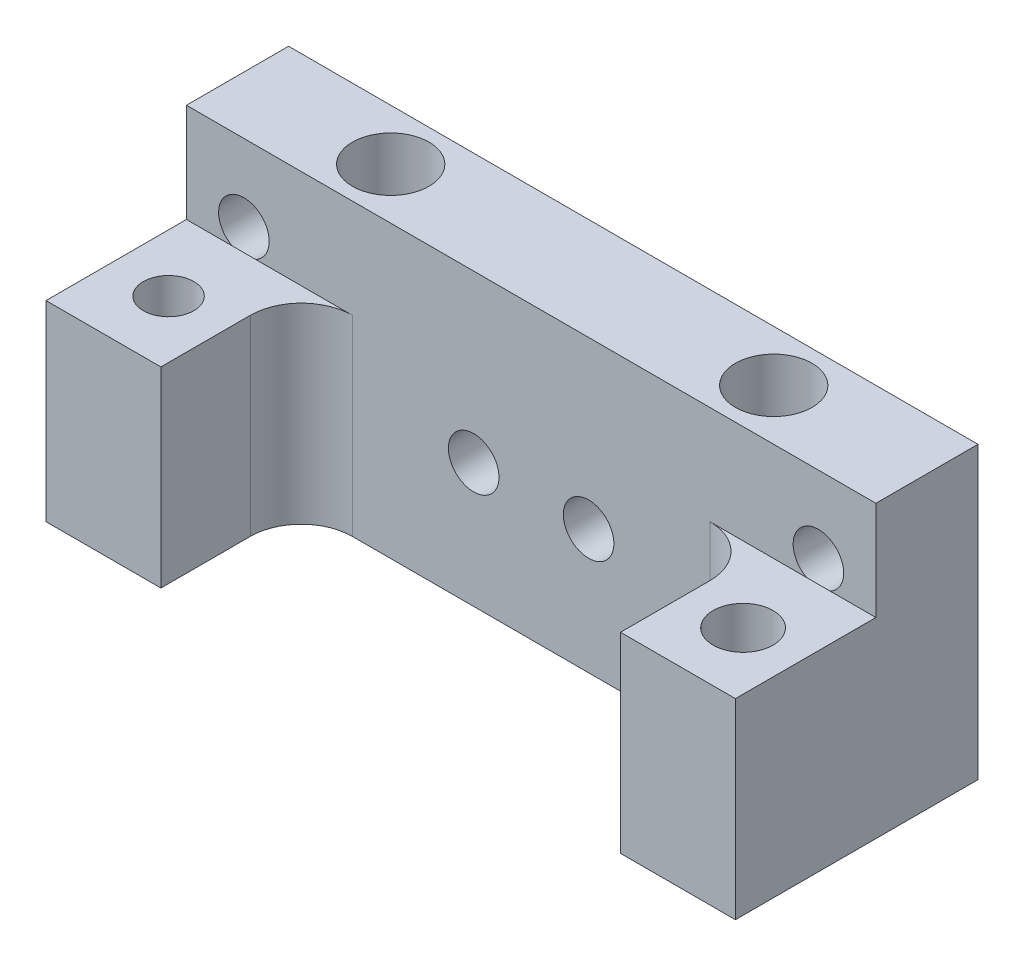
SolidWorks part; units mm, degrees
material "PET"
ref_plane "Front Plane" through (0, 0, 0) normal (0, 0, 1) x (1, 0, 0)
ref_plane "Top Plane" through (0, 0, 0) normal (0, 1, 0) x (1, 0, 0)
ref_plane "Right Plane" through (0, 0, 0) normal (1, 0, 0) x (0, 0, -1)
sketch "Sketch1" plane through (0, 0, 0) normal (0, 1, 0) x (1, 0, 0)
  line L1 (-19, -4) -> (19, -4)
  line L2 (-19, -4) -> (-19, 4)
  line L3 (-19, 4) -> (19, 4)
  line L4 (19, -4) -> (19, 4)
  line L5 (-19, -4) -> (19, 4) construction
  line L6 (-19, 4) -> (19, -4) construction
  point P0 (0, 0)
  dimension "D1" = 8
  dimension "D2" = 38
extrude "Boss-Extrude1" add sketch "Sketch1" along normal blind 22.75
sketch "Sketch9" plane through (0, 0, -4) normal (0, 0, 1) x (1, 0, 0)
  line L1 (-27, 15) -> (-18, 15)
  line L2 (-27, 15) -> (-27, 10)
  line L3 (-27, 10) -> (-18, 10)
  line L4 (27, 15) -> (27, 10)
  line L6 (-19, 0) -> (19, 0) construction
  line L7 (-18, 15) -> (-18, 10)
  line L8 (18, 15) -> (18, 10)
  line L9 (-18, 10) -> (18, 10) construction
  line L10 (18, 10) -> (27, 10)
  line L11 (-18, 15) -> (18, 15) construction
  line L12 (18, 15) -> (27, 15)
  line L13 (-19, 22.75) -> (19, 22.75) construction
  point P4 (-22.5, 15)
  point P5 (22.5, 15)
  point P14 (0, 22.75)
  dimension "D1" = 15
  dimension "D2" = 5
  dimension "D4" = 9
  dimension "D3" = 45
  dimension "D5" = 22.5
extrude "Boss-Extrude2" add sketch "Sketch9" along normal blind 19
sketch "Sketch8" plane through (0, 22.75, 0) normal (0, 1, 0) x (1, 0, 0)
  circle A0 centre (-15, 0) radius 3
  circle A1 centre (15, 0) radius 3
  dimension "D1" = 6
  dimension "D2" = 6
  dimension "D3" = 15
  dimension "D4" = 15
extrude "Cut-Extrude1" cut sketch "Sketch8" against normal blind 18
hole_wizard "CSK for M3 Countersunk Flat Head Screw1" positions "Sketch3" profile "Sketch4" countersink size "M3" standard "ISO"
sketch "Sketch3" plane through (0, 4.75, 0) normal (0, 1, 0) x (1, 0, 0)
  line L0 (0, -10.45) -> (0, 10.45) construction
  line L1 (-12.5125, 0) -> (12.5125, 0) construction
  point P0 (-15, 0)
  point P3 (15, 0)
  dimension "D1" = 30
  dimension "D2" = 15
sketch "Sketch4" plane through (-15, 4.75, 0) normal (1, 0, 0) x (0, 0, 1)
  line L0 (0, 0) -> (0, 4.75)
  line L1 (0, 4.75) -> (1.7, 4.75)
  line L2 (1.7, 4.75) -> (1.7, 1.45)
  line L3 (1.7, 1.45) -> (3.15, 0)
  line L5 (3.15, 0) -> (0, 0)
  line L6 (-1.7, 1.45) -> (-3.15, 0) construction
  line L11 (0, -6.35) -> (0, 107.95) construction
  dimension "Thru Hole Dia." = 3.4
  dimension "Thru Hole Depth" = 4.75
  dimension "Near C'Sink Dia." = 6.3
  dimension "Near C'Sink Angle" = 90
hole_wizard "M3 Clearance Hole1" [suppressed] positions "Sketch10" profile "Sketch11" hole size "M3" standard "ISO"
sketch "Sketch10" plane through (0, 15, 0) normal (0, 1, 0) x (1, 0, 0)
  line L0 (-18.5, -4) -> (-19, -4) construction
  line L1 (19, 4) -> (-19, 4) construction
  point P0 (-22.5, -9.9)
  point P2 (22.5, -9.9)
  point P20 (0, 4)
  dimension "D2" = 45
  dimension "D3" = 5.9
  dimension "D1" = 22.5
sketch "Sketch11" plane through (-22.5, 15, 9.9) normal (1, 0, 0) x (0, 0, 1)
  line L0 (0, 0) -> (0, 15)
  line L1 (0, 15) -> (1.8, 15)
  line L2 (1.8, 15) -> (1.8, 0)
  line L5 (1.8, 0) -> (0, 0)
  line L11 (0, -6.35) -> (0, 107.95) construction
  dimension "Thru Hole Dia." = 3.6
  dimension "Thru Hole Depth" = 15
sketch "Sketch12" [suppressed] plane through (0, 10, 0) normal (0, -1, 0) x (1, 0, 0)
  line L0 (-26.5, 15) -> (-26.5, -4) construction
  line L1 (-26, 11.9207) -> (-26, 7.8793)
  line L2 (-26, 7.8793) -> (-22.5, 5.8585)
  line L3 (-22.5, 5.8585) -> (-19, 7.8793)
  line L4 (-19, 7.8793) -> (-19, 11.9207)
  line L5 (-19, 11.9207) -> (-22.5, 13.9415)
  line L6 (-22.5, 13.9415) -> (-26, 11.9207)
  line L7 (19, 11.9207) -> (19, 7.8793)
  line L8 (19, 7.8793) -> (22.5, 5.8585)
  line L9 (22.5, 5.8585) -> (26, 7.8793)
  line L10 (26, 7.8793) -> (26, 11.9207)
  line L11 (26, 11.9207) -> (22.5, 13.9415)
  line L12 (22.5, 13.9415) -> (19, 11.9207)
  circle A0 centre (-22.5, 9.9) radius 3.5 construction
  circle A1 centre (22.5, 9.9) radius 3.5 construction
  dimension "D1" = 7
extrude "Cut-Extrude2" [suppressed] cut sketch "Sketch12" against normal blind 2
fillet "Fillet1" radius 2 4 edges at (18, 12.5, 15) (-18, 12.5, 15) (-27, 12.5, 15) (27, 12.5, 15)
sketch "Sketch13" plane through (0, 0, 0) normal (0, -1, 0) x (-1, 0, 0)
  line L1 (-18, -4) -> (-27, -4) construction
  line L2 (-18, -4) -> (-18, 4)
  line L3 (-18, 4) -> (-27, 4)
  line L4 (-27, -4) -> (-27, 4)
  line L5 (27, 4) -> (18, 4)
  line L6 (27, 4) -> (27, -4)
  line L7 (27, -4) -> (18, -4) construction
  line L8 (18, 4) -> (18, -4)
  line L9 (18, -4) -> (18, -15)
  line L10 (18, -15) -> (27, -15)
  line L11 (27, -15) -> (27, -4)
  line L12 (25, -15) -> (20, -15) construction
  line L13 (-18, -4) -> (-18, -15)
  line L14 (-18, -15) -> (-27, -15)
  line L15 (-27, -15) -> (-27, -4)
  line L16 (-20, -15) -> (-25, -15) construction
  line L18 (18, -13) -> (18, -4) construction
  line L19 (-18, -13) -> (-18, -4) construction
extrude "Boss-Extrude3" add sketch "Sketch13" against normal up to surface (22.75 mm away) up to face at (-15, 22.75, 3)
hole_wizard "Tap Drill for M3 Tap6" [suppressed] positions "Sketch7" profile "Sketch6" hole size "M3" standard "ISO"
sketch "Sketch7" plane through (0, 0, 4) normal (0, 0, 1) x (1, 0, 0)
  line L0 (0, -4.4) -> (0, 4.4) construction
  line L2 (-26.65, 0) -> (26.65, 0) construction
  point P0 (-22.5, 16.75)
  point P2 (22.5, 16.75)
  point P4 (-3.5, 9.75)
  point P6 (3.5, 9.75)
  dimension "D1" = 3.5
  dimension "D2" = 7
  dimension "D3" = 22.5
  dimension "D4" = 45
  dimension "D5" = 7
  dimension "D6" = 9.75
sketch "Sketch6" plane through (-22.5, 16.75, 4) normal (1, 0, 0) x (0, -1, 0)
  line L0 (0, 0) -> (0, 8)
  line L1 (0, 8) -> (1.25, 8)
  line L2 (1.25, 8) -> (1.25, 0)
  line L5 (1.25, 0) -> (0, 0)
  line L11 (0, -6.35) -> (0, 107.95) construction
  dimension "Thru Hole Dia." = 2.5
  dimension "Thru Hole Depth" = 8
sketch "Sketch14" plane through (0, 22.75, 0) normal (0, 1, 0) x (1, 0, 0)
  line L0 (-27, 4) -> (-27, -15) construction
  line L1 (-27, -4) -> (27, -4)
  line L2 (-27, -4) -> (-27, -15)
  line L3 (-27, -15) -> (27, -15)
  line L4 (27, -4) -> (27, -15)
  line L6 (27, 4) -> (27, -15) construction
  line L7 (-18, -4) -> (18, -4) construction
  line L8 (-27, -15) -> (-18, -15) construction
sketch "Sketch16" plane through (0, 0, -4) normal (0, 0, 1) x (1, 0, 0)
  line L1 (-18, 0) -> (18, 0) construction
  line L3 (0, -10.45) -> (0, 10.45) construction
  circle A0 centre (-22.5, 16.75) radius 1.98
  circle A1 centre (-4.5, 9.75) radius 1.98
  circle A2 centre (4.5, 9.75) radius 1.98
  circle A3 centre (22.5, 16.75) radius 1.98
  point P0 (-22.5, 16.75)
  point P2 (22.5, 16.75)
  point P4 (-4.5, 9.75)
  point P6 (4.5, 9.75)
  dimension "D4" = 45
  dimension "D5" = 7
  dimension "D7" = 3.96
  dimension "D2" = 9
  dimension "D1" = 9.75
  dimension "D3" = 4.5
  dimension "D6" = 22.5
extrude "Cut-Extrude4" cut sketch "Sketch16" along normal blind 8
extrude "Cut-Extrude6" cut sketch "Sketch14" against normal blind 7.75
sketch "Sketch15" plane through (0, 15, 0) normal (0, 1, 0) x (1, 0, 0)
  line L1 (0, -10.45) -> (0, 10.45) construction
  line L2 (-27, -4) -> (27, -4) construction
  circle A0 centre (-22.5, -9.9) radius 1.98
  circle A1 centre (22.5, -9.9) radius 2.35
  dimension "D2" = 45
  dimension "D5" = 22.5
  dimension "D1" = 3.96
  dimension "D3" = 4.7
  dimension "D4" = 5.9
extrude "Cut-Extrude7" cut sketch "Sketch15" against normal blind 4
hole_wizard "M3 Clearance Hole2" positions "Sketch18" profile "Sketch19" hole size "M3" standard "ISO" end condition through all
sketch "Sketch18" plane through (0, 11, 0) normal (0, 1, 0) x (1, 0, 0)
  point P0 (-22.5, -9.9)
  point P3 (22.5, -9.9)
sketch "Sketch19" plane through (-22.5, 11, 9.9) normal (1, 0, 0) x (0, 0, 1)
  line L0 (0, 0) -> (0, 11)
  line L1 (0, 11) -> (1.8, 11)
  line L2 (1.8, 11) -> (1.8, 0)
  line L5 (1.8, 0) -> (0, 0)
  line L11 (0, -6.35) -> (0, 107.95) construction
  dimension "Thru Hole Dia." = 3.6
  dimension "Thru Hole Depth" = 11
fillet "Fillet2" radius 4 2 edges at (18, 7.5, 4) (-18, 7.5, 4)
equation "\"D2@Sketch3\"=\"D1@Sketch3\"/2"
equation "\"D3@Sketch7\"=\"D4@Sketch7\"/2"
equation "\"D4@Sketch8\"=\"D3@Sketch8\""
equation "\"D1@Sketch10\"=\"D2@Sketch10\"/2"
equation "\"D5@Sketch9\"=\"D3@Sketch9\"/2"
equation "\"D5@Sketch15\"=\"D2@Sketch15\"/2"
equation "\"D6@Sketch16\"=\"D4@Sketch16\"/2"
equation "\"D3@Sketch16\"=\"D2@Sketch16\"/2"
